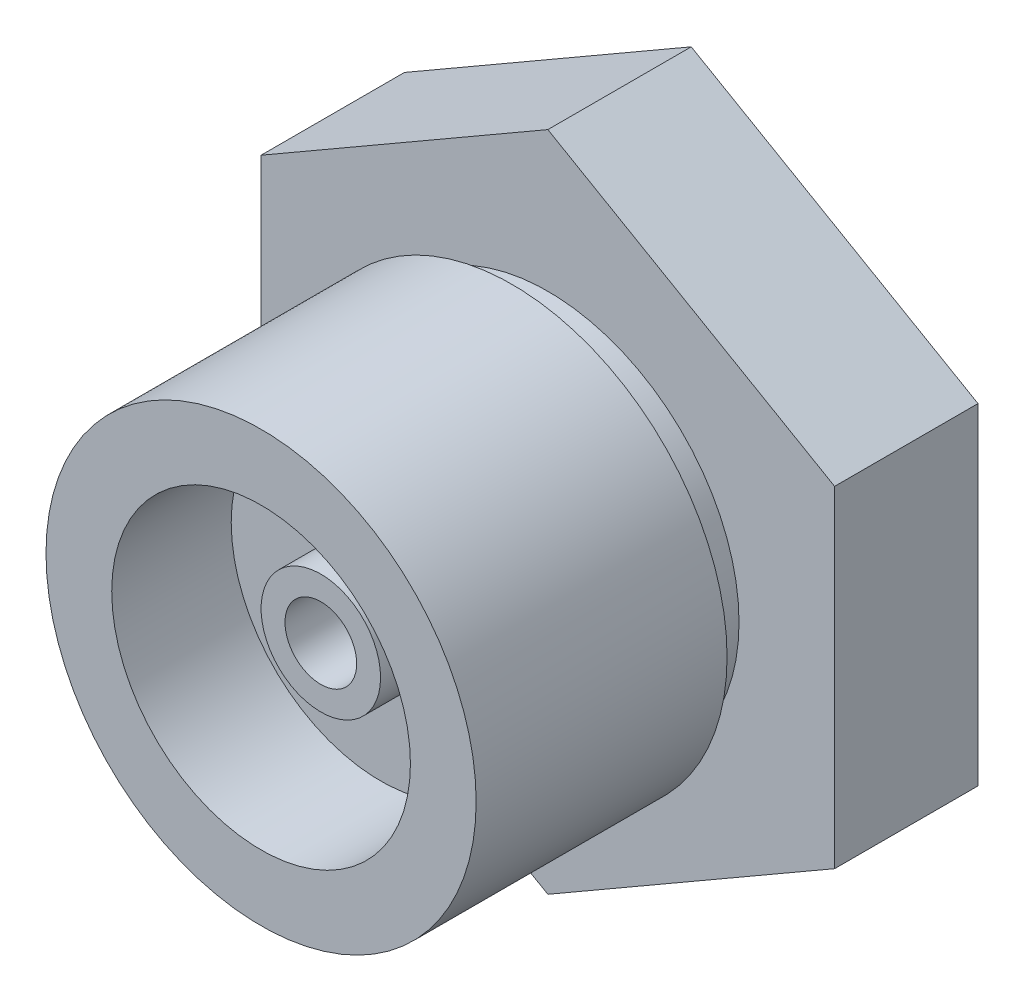
SolidWorks part; units mm, degrees
ref_plane "前视基准面" through (0, 0, 0) normal (0, 0, 1) x (1, 0, 0)
ref_plane "上视基准面" through (0, 0, 0) normal (0, 1, 0) x (1, 0, 0)
ref_plane "右视基准面" through (0, 0, 0) normal (1, 0, 0) x (0, 0, -1)
sketch "草图1" plane through (0, 0, 0) normal (1, 0, 0) x (0, 0, -1)
  line L0 (0, 0) -> (-65.1407, 0) construction
  line L1 (0, 0) -> (0, 24)
  line L2 (0, 24) -> (-12, 24)
  line L3 (-12, 24) -> (-12, 16)
  line L4 (-12, 16) -> (-15, 16)
  line L5 (-15, 16) -> (-15, 18)
  line L6 (-15, 18) -> (-36, 18)
  line L7 (-36, 18) -> (-36, 0)
  line L8 (0, 0) -> (-36, 0)
  point P6 (-12, 9.9527)
  dimension "D1" = 36
  dimension "D2" = 3
  dimension "D3" = 12
  dimension "D4" = 36
  dimension "D5" = 48
  dimension "D6" = 32
revolve "旋转1" add sketch "草图1" angle 360 about L0
cosmetic thread "装饰螺纹线1" parameters "D2"=35
sketch "草图2" plane through (0, 0, 36) normal (0, 0, 1) x (1, 0, 0)
  circle A0 centre (0, 0) radius 12.5
  circle A1 centre (0, 0) radius 5
  dimension "D1" = 25
  dimension "D2" = 10
extrude "切除-拉伸1" cut sketch "草图2" against normal blind 10
sketch "草图3" plane through (0, 0, 36) normal (0, 0, 1) x (1, 0, 0)
  circle A0 centre (0, 0) radius 3
  dimension "D1" = 6
extrude "切除-拉伸2" cut sketch "草图3" against normal blind 10
sketch "草图4" plane through (0, 0, 36) normal (0, 0, 1) x (1, 0, 0)
  circle A1 centre (0, 0) radius 5
  circle A2 centre (0, 0) radius 5
  dimension "D1" = 0
extrude "切除-拉伸3" cut sketch "草图4" against normal blind 5
sketch "草图5" plane through (0, 0, 0) normal (0, 0, -1) x (-1, 0, 0)
  line L0 (0, 0) -> (0, 27.7128) construction
  line L1 (0, 27.7128) -> (-24, 13.8564)
  line L2 (-24, 13.8564) -> (-24, -13.8564)
  line L3 (-24, -13.8564) -> (0, -27.7128)
  line L4 (0, -27.7128) -> (24, -13.8564)
  line L5 (24, -13.8564) -> (24, 13.8564)
  line L6 (24, 13.8564) -> (0, 27.7128)
  circle A0 centre (0, 0) radius 24 construction
  dimension "D1" = 48
extrude "凸台-拉伸1" add sketch "草图5" against normal up to surface (12 mm away) up to face at (-16, 0, 12)
